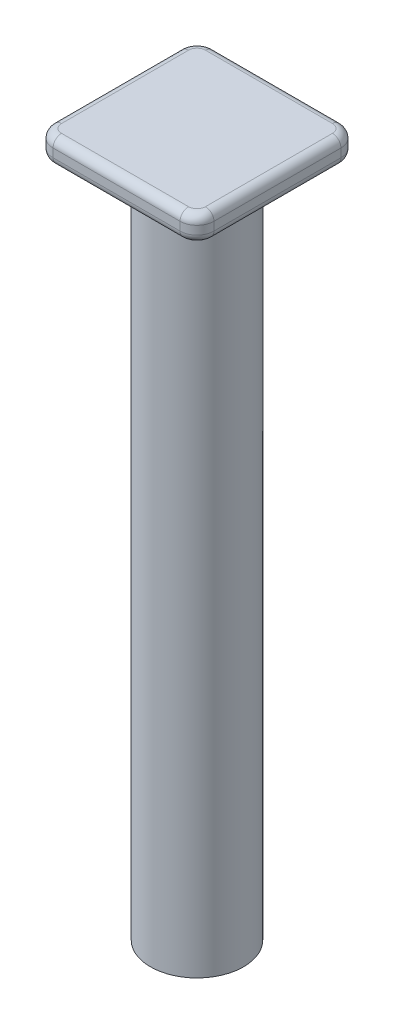
SolidWorks part; units mm, degrees
ref_plane "Front Plane" through (0, 0, 0) normal (0, 0, 1) x (1, 0, 0)
ref_plane "Top Plane" through (0, 0, 0) normal (0, 1, 0) x (1, 0, 0)
ref_plane "Right Plane" through (0, 0, 0) normal (1, 0, 0) x (0, 0, -1)
sketch "Sketch1" plane through (0, 0, 0) normal (0, 1, 0) x (1, 0, 0)
  line L0 (-6.0325, -4.7625) -> (-6.0325, 4.7625)
  line L5 (-4.1275, -4.1275) -> (4.1275, 4.1275) construction
  line L6 (-4.1275, 4.1275) -> (4.1275, -4.1275) construction
  line L7 (-4.7625, 6.0325) -> (4.7625, 6.0325)
  line L8 (6.0325, -4.7625) -> (6.0325, 4.7625)
  line L9 (-4.7625, -6.0325) -> (4.7625, -6.0325)
  arc A4 (4.7625, 6.0325) -> (6.0325, 4.7625) centre (4.7625, 4.7625) cw
  arc A5 (6.0325, -4.7625) -> (4.7625, -6.0325) centre (4.7625, -4.7625) cw
  arc A6 (-6.0325, -4.7625) -> (-4.7625, -6.0325) centre (-4.7625, -4.7625) ccw
  arc A7 (-6.0325, 4.7625) -> (-4.7625, 6.0325) centre (-4.7625, 4.7625) cw
  point P0 (0, 0)
  dimension "D4" = 1.27
  dimension "D2" = 8.255
extrude "Boss-Extrude1" add sketch "Sketch1" along normal blind 1.905
sketch "Sketch2" plane through (0, 0, 0) normal (0, -1, 0) x (1, 0, 0)
  circle A0 centre (0, 0) radius 2.54
  circle A1 centre (0, 0) radius 3.4925
  dimension "D1" = 0.9525
  dimension "D2" = 6.985
extrude "Boss-Extrude2" add sketch "Sketch2" along normal blind 50.8
fillet "Fillet2" radius 0.635 16 edges at (5.6605, 0, -5.6605) (6.0325, 0, 0) (5.6605, 0, 5.6605) (0, 0, 6.0325) (-5.6605, 0, 5.6605) (-6.0325, 0, 0) (-5.6605, 0, -5.6605) (5.6605, 1.905, -5.6605) (6.0325, 1.905, 0) (5.6605, 1.905, 5.6605) (0, 1.905, 6.0325) (-5.6605, 1.905, 5.6605) (-6.0325, 1.905, 0) (-5.6605, 1.905, -5.6605) (0, 0, -6.0325) (0, 1.905, -6.0325)
scale "Scale1" bodies to scale 102 scale about centroid uniform scaling yes scale factor 1.5
